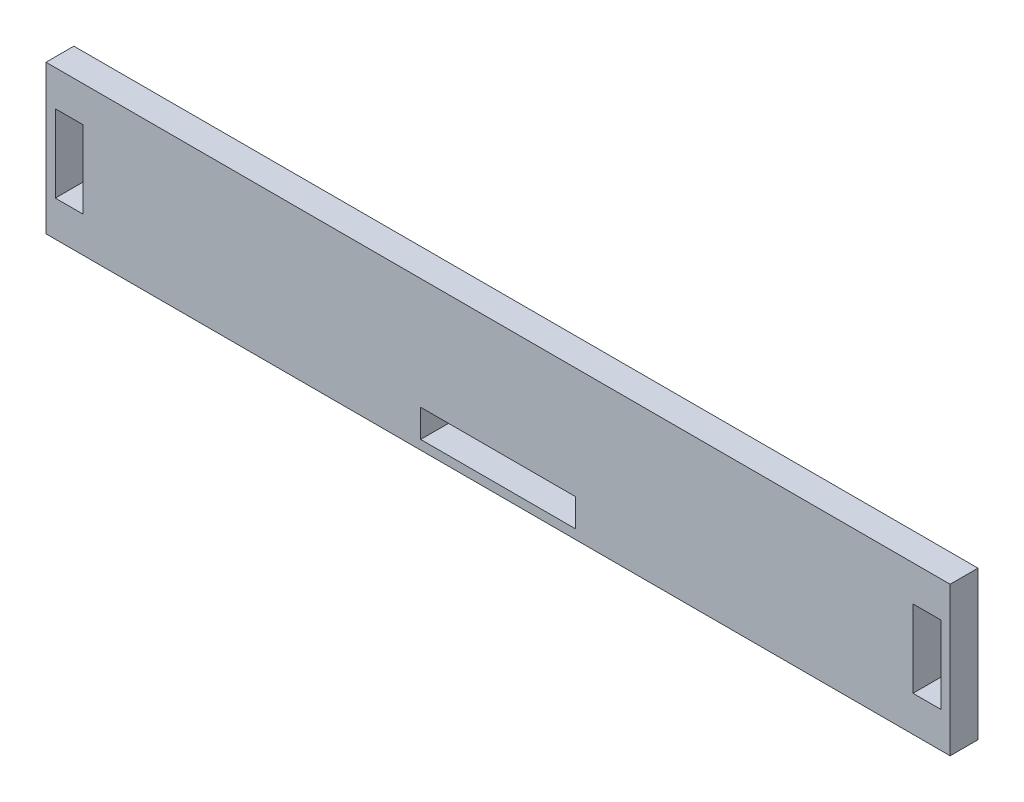
SolidWorks part; units mm, degrees
ref_plane "Front Plane" through (0, 0, 0) normal (0, 0, 1) x (1, 0, 0)
ref_plane "Top Plane" through (0, 0, 0) normal (0, 1, 0) x (1, 0, 0)
ref_plane "Right Plane" through (0, 0, 0) normal (1, 0, 0) x (0, 0, -1)
sketch "Sketch1" plane through (0, 0, 0) normal (0, 0, 1) x (1, 0, 0)
  line L1 (0, 0) -> (584, 0)
  line L2 (0, 0) -> (0, 96)
  line L3 (0, 96) -> (584, 96)
  line L4 (584, 0) -> (584, 96)
  line L5 (0, 48) -> (61.7792, 48) construction
  line L6 (242, 6) -> (342, 6)
  line L7 (242, 6) -> (242, 24)
  line L8 (242, 24) -> (342, 24)
  line L9 (342, 6) -> (342, 24)
  line L12 (578, 23) -> (560, 23)
  line L13 (6, 73) -> (24, 73)
  line L14 (6, 73) -> (6, 23)
  line L15 (6, 23) -> (24, 23)
  line L16 (24, 73) -> (24, 23)
  line L19 (578, 73) -> (578, 23)
  line L20 (578, 73) -> (560, 73)
  line L21 (560, 73) -> (560, 23)
  point P7 (292, 15)
  point P14 (15, 48)
  dimension "D1" = 584
  dimension "D2" = 96
  dimension "D3" = 6
  dimension "D4" = 18
  dimension "D5" = 100
  dimension "D6" = 6
  dimension "D7" = 18
  dimension "D8" = 50
extrude "Boss-Extrude6" add sketch "Sketch1" along normal blind 18
